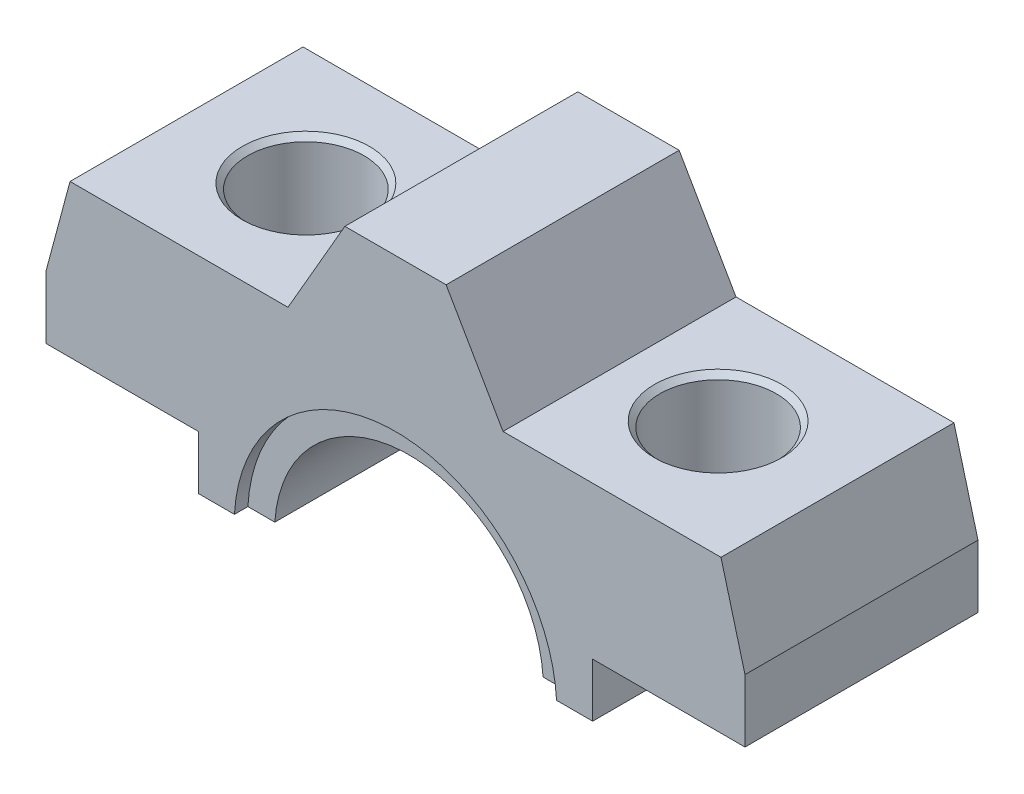
SolidWorks part; units mm, degrees
material "Простая углеродистая сталь"
ref_plane "Спереди" through (0, 0, 0) normal (0, 0, 1) x (1, 0, 0)
ref_plane "Сверху" through (0, 0, 0) normal (0, 1, 0) x (1, 0, 0)
ref_plane "Справа" through (0, 0, 0) normal (1, 0, 0) x (0, 0, -1)
sketch "Эскиз1" plane through (0, 0, 0) normal (0, 0, 1) x (1, 0, 0)
  line L0 (-75.5144, 7) -> (79.0283, 7) construction
  line L1 (0, -29.7379) -> (0, 81.53) construction
  line L2 (-35.0999, 24) -> (-12, 24)
  line L3 (-12, 24) -> (-5.6491, 35)
  line L4 (-5.6491, 35) -> (5.6491, 35)
  line L5 (5.6491, 35) -> (12, 24)
  line L6 (12, 24) -> (35.0999, 24)
  line L7 (-39, 7) -> (-22, 7)
  line L8 (-22, 7) -> (-22, 1)
  line L9 (-22, 0) -> (22, 0) construction
  line L10 (-22, 1) -> (22, 1)
  line L11 (22, 1) -> (22, 7)
  line L12 (22, 7) -> (39, 7)
  line L13 (12, 24) -> (12, 27.3464) construction
  arc A0 (39, 7) -> (35.0999, 24) centre (0, 7) ccw
  arc A2 (-35.0999, 24) -> (-39, 7) centre (0, 7) ccw
  dimension "D1" = 44
  dimension "D2" = 39
  dimension "D4" = 1
  dimension "D3" = 7
  dimension "D5" = 24
  dimension "D6" = 24
  dimension "D7" = 30
  dimension "D8" = 35
extrude "Бобышка-Вытянуть1" add sketch "Эскиз1" against normal blind 26
sketch "Эскиз2" plane through (0, 0, 0) normal (0, 0, 1) x (1, 0, 0)
  line L0 (-22, 0) -> (22, 0) construction
  line L1 (-22, 0) -> (22, 0) construction
  line L2 (0, -29.7379) -> (0, 81.53) construction
  line L3 (0, -29.7379) -> (0, 81.53) construction
  circle A0 centre (0, 0) radius 15
  dimension "D1" = 30
extrude "Вырез-Вытянуть1" cut sketch "Эскиз2" against normal through all
sketch "Эскиз3" plane through (0, 0, 0) normal (0, 0, 1) x (1, 0, 0)
  line L0 (-22, 0) -> (22, 0) construction
  line L1 (0, -29.7379) -> (0, 81.53) construction
  line L2 (-22, 0) -> (22, 0) construction
  line L3 (0, -29.7379) -> (0, 81.53) construction
  circle A0 centre (0, 0) radius 18
  dimension "D1" = 36
extrude "Вырез-Вытянуть2" cut sketch "Эскиз3" against normal blind 1.5
sketch "Эскиз4" plane through (0, 0, -26) normal (0, 0, -1) x (-1, 0, 0)
  line L0 (22, 0) -> (-22, 0) construction
  line L1 (0, -29.7379) -> (0, 81.53) construction
  line L2 (22, 0) -> (-22, 0) construction
  line L3 (0, -29.7379) -> (0, 81.53) construction
  circle A0 centre (0, 0) radius 18
  dimension "D1" = 36
extrude "Вырез-Вытянуть3" cut sketch "Эскиз4" against normal blind 1.5
sketch "Эскиз9" plane through (0, 0, 0) normal (0, 0, 1) x (1, 0, 0)
  line L6 (-39, 7) -> (-39, 14)
  line L7 (39, 7) -> (39, 14)
  line L8 (-39, 14) -> (-36.3205, 24)
  line L9 (39, 14) -> (36.3205, 24)
  line L10 (-22, 7) -> (-22, 24)
  line L11 (22, 7) -> (22, 24)
  line L15 (22, 1) -> (22, 7)
  line L16 (22, 7) -> (39, 7)
  line L17 (35.0999, 24) -> (12, 24)
  line L18 (12, 24) -> (5.6491, 35)
  line L19 (5.6491, 35) -> (-5.6491, 35)
  line L20 (-5.6491, 35) -> (-12, 24)
  line L21 (-12, 24) -> (-35.0999, 24)
  line L22 (-39, 7) -> (-22, 7)
  line L23 (-22, 7) -> (-22, 1)
  line L24 (-22, 1) -> (22, 1)
  line L26 (22, 7) -> (39, 7)
  line L27 (36.3205, 24) -> (22, 24)
  line L31 (-22, 24) -> (-36.3205, 24)
  line L32 (-39, 7) -> (-22, 7)
  arc A2 (39, 7) -> (35.0999, 24) centre (0, 7) ccw
  arc A3 (-35.0999, 24) -> (-39, 7) centre (0, 7) ccw
  dimension "D2" = 10
  dimension "D3" = 15
  dimension "D4" = 10
  dimension "D5" = 15
  dimension "D6" = 78
  dimension "D1" = 0
extrude "Бобышка-Вытянуть2" add sketch "Эскиз9" against normal up to surface (26 mm away) up to face at (0, 15.3887, -26)
sketch "Эскиз6" plane through (0, 24, 0) normal (0, 1, 0) x (1, 0, 0)
  line L0 (-46.5747, 13) -> (44.1615, 13) construction
  line L1 (0, -15.7573) -> (0, 36.046) construction
  circle A0 centre (-23, 13) radius 6.5
  circle A1 centre (23, 13) radius 6.5
  dimension "D4" = 13
  dimension "D5" = 13
  dimension "D1" = 13
  dimension "D2" = 46
  dimension "D3" = 23
extrude "Вырез-Вытянуть5" cut sketch "Эскиз6" against normal through all
chamfer "Фаска1" distance 0.6 angle 45 2 edges at (23, 24, -6.5) (-23, 24, -6.5)
